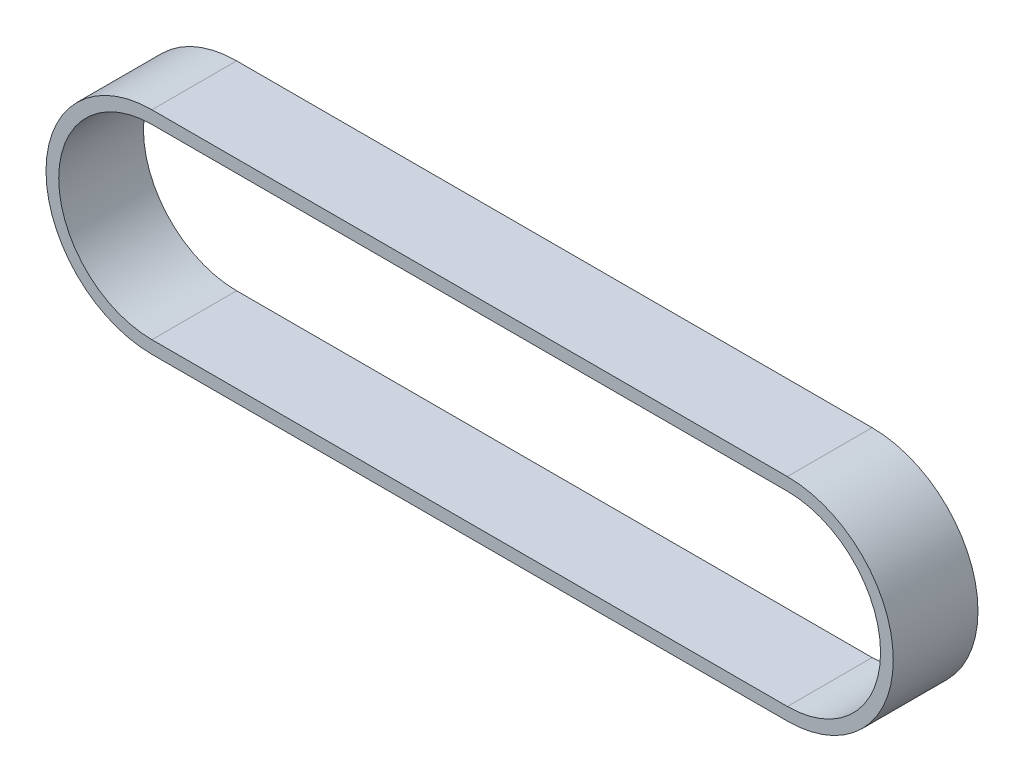
SolidWorks part; units mm, degrees
material "Rubber"
ref_plane "Front Plane" through (0, 0, 0) normal (0, 0, 1) x (1, 0, 0)
ref_plane "Top Plane" through (0, 0, 0) normal (0, 1, 0) x (1, 0, 0)
ref_plane "Right Plane" through (0, 0, 0) normal (1, 0, 0) x (0, 0, -1)
sketch "Sketch2" plane through (0, 0, 0) normal (0, 0, 1) x (1, 0, 0)
  line L0 (0, 0) -> (1, 0) construction
  line L1 (0, 0) -> (0, 1) construction
  line L2 (-0.0062, 44) -> (299.9938, 44.0423)
  line L3 (300.0062, -43.9577) -> (0.0062, -44)
  arc A0 (0.0062, -44) -> (-0.0062, 44) centre (0, 0) cw
  arc A1 (299.9938, 44.0423) -> (300.0062, -43.9577) centre (300, 0.0423) cw
extrude "Extrude-Thin1" add sketch "Sketch2" along normal mid plane 40 thin thin type one direction wall 6
